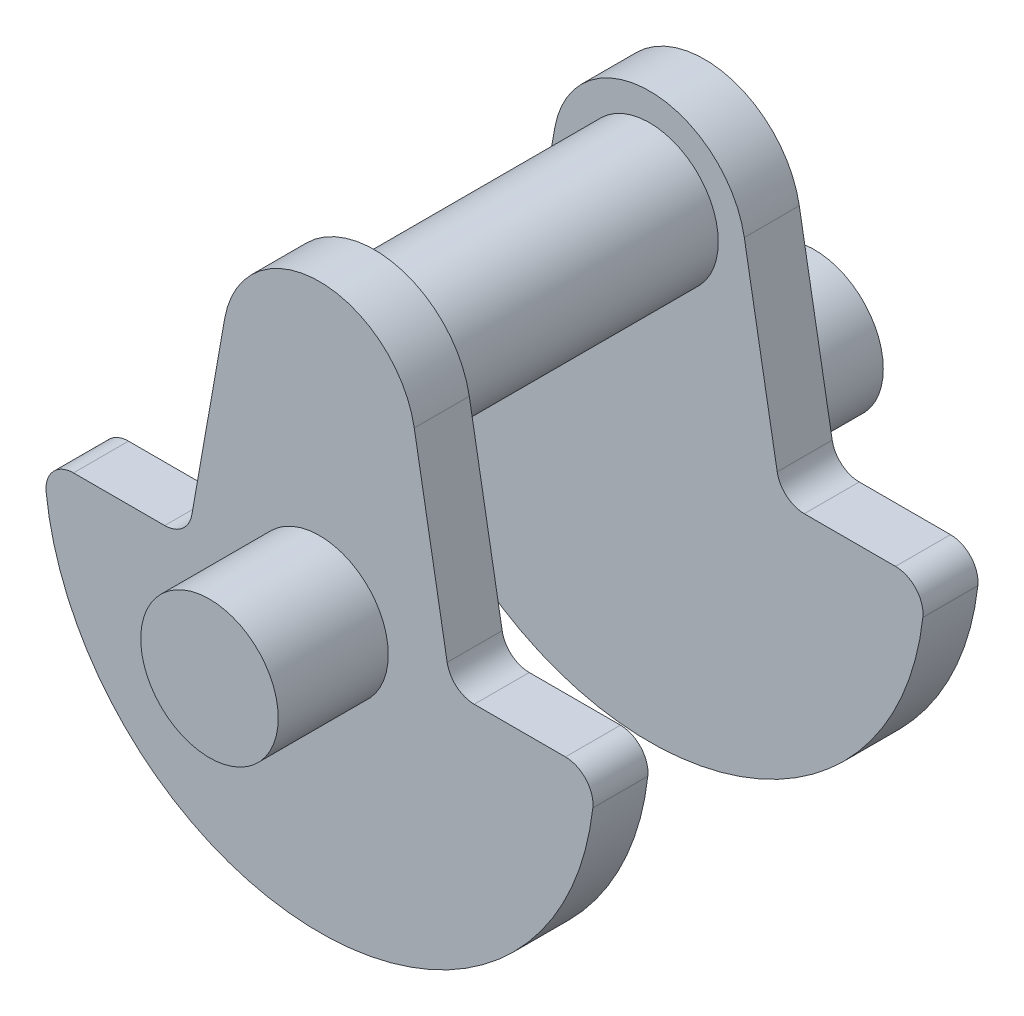
SolidWorks part; units mm, degrees
material "Plain Carbon Steel"
ref_plane "Front Plane" through (0, 0, 0) normal (0, 0, 1) x (1, 0, 0)
ref_plane "Top Plane" through (0, 0, 0) normal (0, 1, 0) x (1, 0, 0)
ref_plane "Right Plane" through (0, 0, 0) normal (1, 0, 0) x (0, 0, -1)
sketch "Sketch1" plane through (0, 0, 0) normal (0, 0, 1) x (1, 0, 0)
  line L0 (0, 0) -> (0, -35) construction
  line L1 (-44.7214, -35) -> (-28.1369, -35)
  line L2 (-17.2341, 3.0388) -> (-23.2129, -30.8682)
  line L3 (17.2341, 3.0388) -> (23.2129, -30.8682)
  line L4 (28.1369, -35) -> (44.7214, -35)
  arc A0 (17.2341, 3.0388) -> (-17.2341, 3.0388) centre (0, 0) ccw
  arc A4 (-49.6904, -40.5556) -> (49.6904, -40.5556) centre (0, -35) ccw
  arc A5 (-44.7214, -35) -> (-49.6904, -40.5556) centre (-44.7214, -40) ccw
  arc A6 (44.7214, -35) -> (49.6904, -40.5556) centre (44.7214, -40) cw
  arc A7 (23.2129, -30.8682) -> (28.1369, -35) centre (28.1369, -30) ccw
  arc A8 (-23.2129, -30.8682) -> (-28.1369, -35) centre (-28.1369, -30) cw
  point P11 (-50, -35)
  point P14 (50, -35)
  point P17 (23.9414, -35)
  point P20 (-23.9414, -35)
  dimension "D1" = 35
  dimension "D2" = 35
  dimension "D4" = 10
  dimension "D3" = 50
  dimension "D5" = 5
  dimension "D6" = 5
  dimension "D7" = 5
extrude "Boss-Extrude1" add sketch "Sketch1" along normal blind 10
sketch "Sketch2" plane through (0, 0, 10) normal (0, 0, 1) x (1, 0, 0)
  circle A0 centre (0, -35) radius 12.5
  dimension "D1" = 25
extrude "Boss-Extrude2" add sketch "Sketch2" along normal blind 20
sketch "Sketch3" plane through (0, 0, 0) normal (0, 0, -1) x (-1, 0, 0)
  circle A0 centre (0, 0) radius 12.5
  dimension "D1" = 25
extrude "Boss-Extrude4" add sketch "Sketch3" along normal blind 25
mirror "Mirror2" about plane through (0, 0, -25) normal (0, 0, -1) of bodies 105
